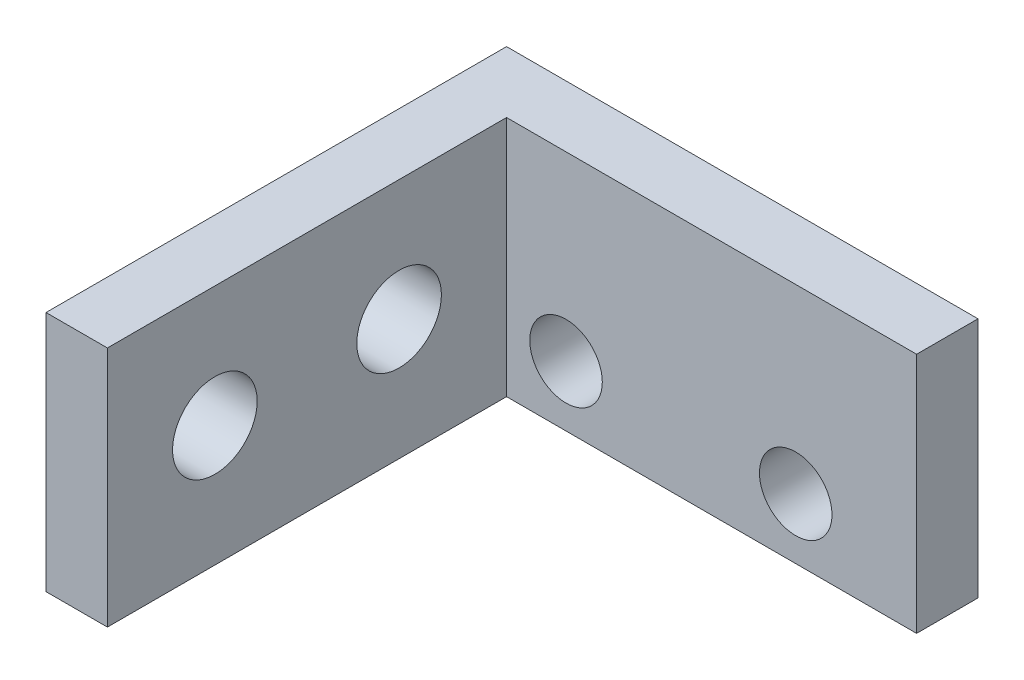
SolidWorks part; units mm, degrees
material "PLA"
ref_plane "Front Plane" through (0, 0, 0) normal (0, 0, 1) x (1, 0, 0)
ref_plane "Top Plane" through (0, 0, 0) normal (0, 1, 0) x (1, 0, 0)
ref_plane "Right Plane" through (0, 0, 0) normal (1, 0, 0) x (0, 0, -1)
sketch "Sketch2" plane through (0, 0, 0) normal (0, 0, 1) x (1, 0, 0)
  line L0 (-4.75, -2.5) -> (4.75, -2.5) construction
  line L1 (-9.75, -5) -> (9.75, -5)
  line L2 (-9.75, -5) -> (-9.75, 5)
  line L3 (-9.75, 5) -> (9.75, 5)
  line L4 (9.75, -5) -> (9.75, 5)
  line L5 (-9.75, -5) -> (9.75, 5) construction
  line L6 (-9.75, 5) -> (9.75, -5) construction
  circle A0 centre (-4.75, -2.5) radius 1.5
  circle A1 centre (4.75, -2.5) radius 1.5
  point P0 (0, 0)
  dimension "D6" = 3
  dimension "D1" = 19.5
  dimension "D2" = 10
  dimension "D3" = 5
  dimension "D4" = 5
  dimension "D5" = 2.5
extrude "Boss-Extrude1" add sketch "Sketch2" along normal mid plane 2.54
sketch "Sketch3" plane through (-9.75, 0, 0) normal (-1, 0, 0) x (0, 0, 1)
  line L1 (-1.27, -5) -> (17.78, -5)
  line L2 (-1.27, -5) -> (-1.27, 5)
  line L3 (-1.27, 5) -> (17.78, 5)
  line L4 (17.78, -5) -> (17.78, 5)
  dimension "D1" = 19.05
extrude "Boss-Extrude2" add sketch "Sketch3" against normal blind 2.54
sketch "Sketch4" plane through (-7.21, 0, 0) normal (1, 0, 0) x (0, 0, -1)
  line L0 (-17.78, 0) -> (-13.335, 0) construction
  line L1 (-17.78, -5) -> (-17.78, 5) construction
  line L2 (-13.335, 0) -> (-5.715, 0) construction
  line L3 (-5.715, 0) -> (-1.27, 0) construction
  line L4 (-1.27, 5) -> (-1.27, -5) construction
  circle A0 centre (-5.715, 0) radius 1.75
  circle A1 centre (-13.335, 0) radius 1.75
  dimension "D1" = 3.5
  dimension "D2" = 7.62
extrude "Cut-Extrude1" cut sketch "Sketch4" against normal through all
